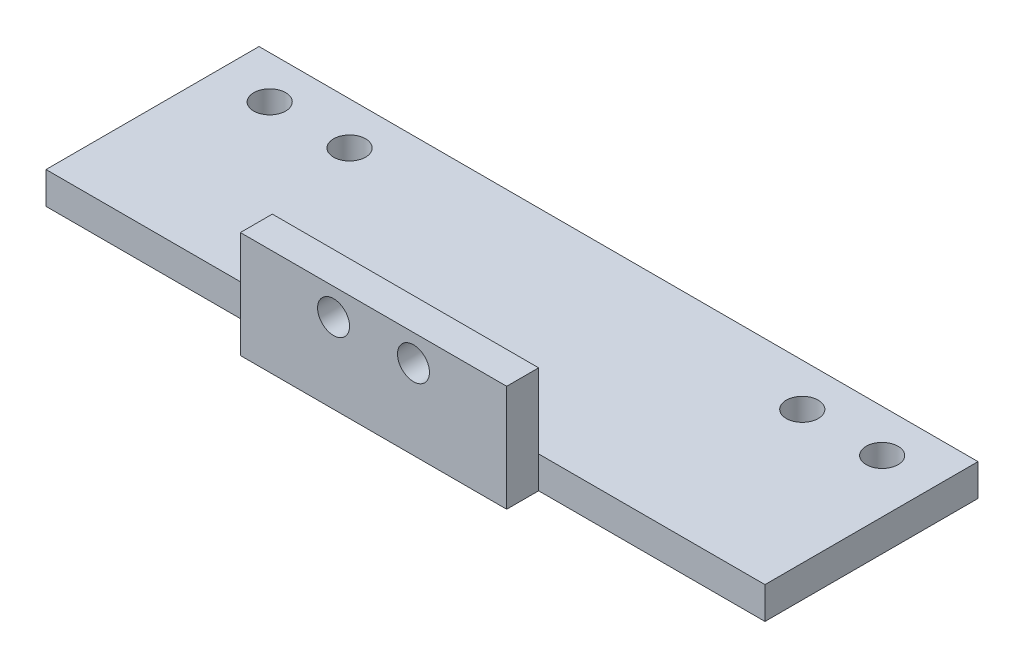
SolidWorks part; units mm, degrees
ref_plane "Front Plane" through (0, 0, 0) normal (0, 0, 1) x (1, 0, 0)
ref_plane "Top Plane" through (0, 0, 0) normal (0, 1, 0) x (1, 0, 0)
ref_plane "Right Plane" through (0, 0, 0) normal (1, 0, 0) x (0, 0, -1)
sketch "Sketch1" plane through (0, 0, 0) normal (0, 1, 0) x (1, 0, 0)
  line L1 (-25, 3) -> (25, 3)
  line L2 (-25, 3) -> (-25, -3)
  line L3 (-25, -3) -> (25, -3)
  line L4 (25, 3) -> (25, -3)
  line L5 (-25, 3) -> (25, -3) construction
  line L6 (-25, -3) -> (25, 3) construction
  point P0 (0, 0)
  dimension "D1" = 50
  dimension "D2" = 6
extrude "Boss-Extrude1" add sketch "Sketch1" along normal blind 20
sketch "Sketch2" plane through (0, 0, -3) normal (0, 0, -1) x (-1, 0, 0)
  line L0 (-7.5, 15) -> (-25, 15) construction
  line L1 (-25, 20) -> (-25, 0) construction
  line L2 (-7.5, 15) -> (-7.5, 20) construction
  line L3 (-25, 20) -> (25, 20) construction
  line L4 (-7.5, 15) -> (7.5, 15) construction
  line L5 (7.5, 15) -> (25, 15) construction
  line L6 (25, 20) -> (25, 0) construction
  circle A0 centre (-7.5, 15) radius 3
  circle A1 centre (7.5, 15) radius 3
  dimension "D1" = 6
  dimension "D3" = 15
  dimension "D4" = 5
  dimension "D2" = 2
extrude "Cut-Extrude1" cut sketch "Sketch2" against normal through all
sketch "Sketch3" plane through (0, 0, -3) normal (0, 0, -1) x (-1, 0, 0)
  line L0 (-25, 0) -> (25, 0) construction
  line L1 (-67.5, 6) -> (67.5, 6)
  line L2 (-67.5, 6) -> (-67.5, 0)
  line L3 (-67.5, 0) -> (67.5, 0)
  line L4 (67.5, 6) -> (67.5, 0)
  line L5 (-67.5, 6) -> (67.5, 0) construction
  line L6 (-67.5, 0) -> (67.5, 6) construction
  point P0 (0, 3)
  point P7 (0, 0)
  point P8 (0, 0)
  dimension "D1" = 6
  dimension "D2" = 135
extrude "Boss-Extrude2" add sketch "Sketch3" along normal blind 40
sketch "Sketch4" plane through (0, 6, 0) normal (0, 1, 0) x (1, 0, 0)
  line L0 (-57.5, 35) -> (-67.5, 35) construction
  line L1 (-67.5, 43) -> (-67.5, 3) construction
  line L2 (-57.5, 35) -> (-57.5, 43) construction
  line L3 (-67.5, 43) -> (67.5, 43) construction
  line L4 (-57.5, 35) -> (-42.5, 35) construction
  line L5 (0, 43) -> (0, 3) construction
  line L6 (-25, 3) -> (25, 3) construction
  line L7 (57.5, 35) -> (42.5, 35) construction
  line L8 (57.5, 35) -> (57.5, 43) construction
  line L9 (57.5, 35) -> (67.5, 35) construction
  circle A0 centre (-57.5, 35) radius 3
  circle A1 centre (-42.5, 35) radius 3
  circle A2 centre (42.5, 35) radius 3
  circle A3 centre (57.5, 35) radius 3
  point P22 (-42.5, 33.4083)
  dimension "D3" = 6
  dimension "D2" = 15
  dimension "D4" = 10
  dimension "D5" = 8
  dimension "D1" = 2
extrude "Cut-Extrude2" cut sketch "Sketch4" against normal through all
